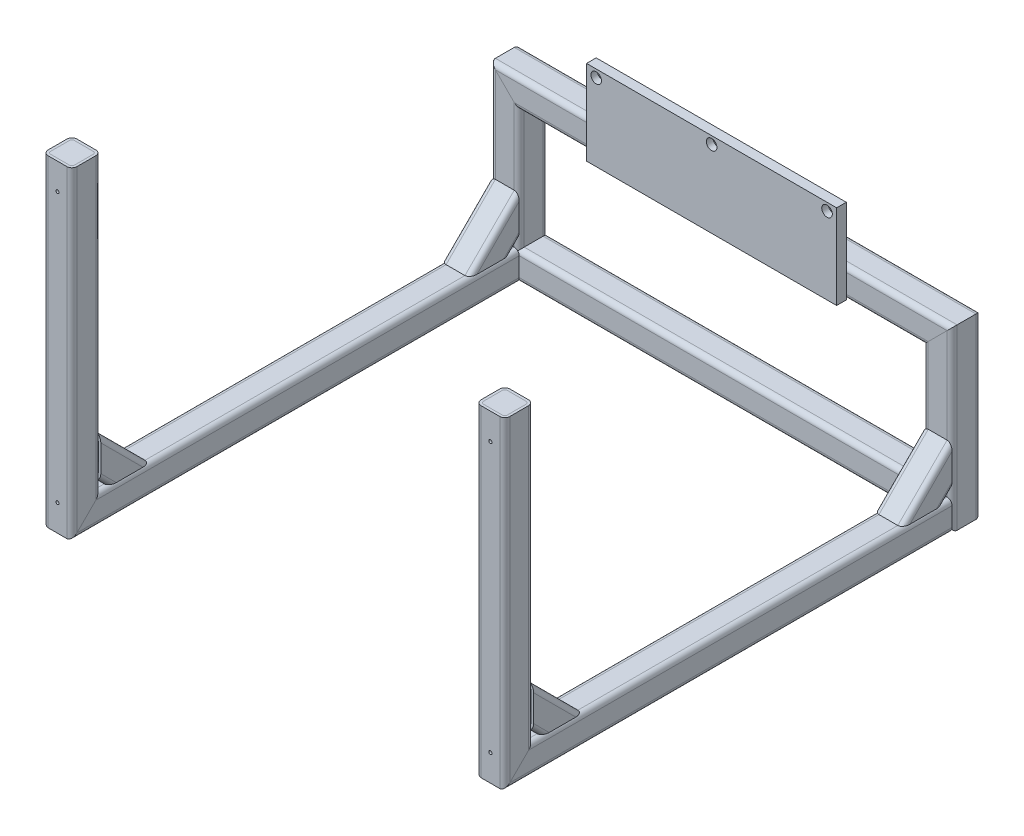
SolidWorks part; units mm, degrees
material "Q235"
ref_plane "前视" through (0, 0, 0) normal (0, 0, 1) x (1, 0, 0)
ref_plane "上视" through (0, 0, 0) normal (0, 1, 0) x (1, 0, 0)
ref_plane "右视" through (0, 0, 0) normal (1, 0, 0) x (0, 0, -1)
sketch3d "3D草图1"
  line L0 (0, 0, 0) -> (0, 0, -67.6759) construction
  line L1 (-225, 0, 0) -> (225, 0, 0)
  line L2 (-225, 0, 0) -> (-225, -155, 0)
  line L3 (-225, -155, 0) -> (-225, -155, 465)
  line L4 (-225, -155, 465) -> (-225, 165, 465)
  line L5 (225, 0, 0) -> (225, -155, 0)
  line L6 (225, -155, 0) -> (225, -155, 465)
  line L7 (225, -155, 465) -> (225, 165, 465)
  line L8 (-225, -155, 0) -> (225, -155, 0)
  line L9 (-225, 165, 465) -> (225, 165, 465) construction
  line L10 (-225, -155, 465) -> (225, -155, 465) construction
  line L11 (-225, -95, 465) -> (-225, -155, 405)
  line L12 (-225, -95, 0) -> (-225, -155, 60)
  line L13 (225, -95, 0) -> (225, -155, 60)
  line L14 (225, -95, 465) -> (225, -155, 405)
  line L15 (-225, -155, 60) -> (225, -155, 60) construction
  line L16 (-225, -155, 405) -> (225, -155, 405) construction
  line L17 (-225, -95, 465) -> (225, -95, 465) construction
  line L18 (-225, -95, 0) -> (225, -95, 0) construction
  dimension "D1" = 450
  dimension "D2" = 465
  dimension "D3" = 320
  dimension "D4" = 155
  dimension "D5" = 45
  dimension "D6" = 45
  dimension "D7" = 60
  dimension "D8" = 60
other "结构构件5"
ref_plane "基准面7" through (-225, 0, 0) normal (0, -1, 0) x (1, 0, 0)
sketch "Sketch1" plane through (-225, 0, 0) normal (0, -1, 0) x (1, 0, 0)
  line L0 (-9.8, -12.4) -> (9.8, -12.4)
  line L1 (-12.4, -9.8) -> (-12.4, 9.8)
  line L2 (9.8, 12.4) -> (-9.8, 12.4)
  line L3 (12.4, 9.8) -> (12.4, -9.8)
  line L4 (-9.8, -15) -> (9.8, -15)
  line L5 (-15, -9.8) -> (-15, 9.8)
  line L6 (9.8, 15) -> (-9.8, 15)
  line L7 (15, 9.8) -> (15, -9.8)
  arc A0 (15, 9.8) -> (9.8, 15) centre (9.8, 9.8) ccw
  arc A1 (9.8, -15) -> (15, -9.8) centre (9.8, -9.8) ccw
  arc A2 (-15, -9.8) -> (-9.8, -15) centre (-9.8, -9.8) ccw
  arc A3 (-9.8, 15) -> (-15, 9.8) centre (-9.8, 9.8) ccw
  arc A4 (-9.8, 12.4) -> (-12.4, 9.8) centre (-9.8, 9.8) ccw
  arc A5 (12.4, 9.8) -> (9.8, 12.4) centre (9.8, 9.8) ccw
  arc A6 (9.8, -12.4) -> (12.4, -9.8) centre (9.8, -9.8) ccw
  arc A7 (-12.4, -9.8) -> (-9.8, -12.4) centre (-9.8, -9.8) ccw
  point P0 (-15, 0)
  point P1 (15, 0)
  point P2 (0, 15)
  point P3 (0, -15)
  point P4 (0, 0)
  point P5 (-15, -15)
  point P6 (15, -15)
  point P7 (15, 15)
  point P8 (-15, 15)
  point P33 (0, 0)
  dimension "D1" = 5.2
  dimension "Thickness" = 2.6
  dimension "V_leg" = 30
other "结构构件6"
ref_plane "基准面8" through (225, -155, 0) normal (0, 0, 1) x (1, 0, 0)
sketch "Sketch15" plane through (225, -155, 0) normal (0, 0, 1) x (1, 0, 0)
  line L0 (-9.8, -12.4) -> (9.8, -12.4)
  line L1 (-12.4, -9.8) -> (-12.4, 9.8)
  line L2 (9.8, 12.4) -> (-9.8, 12.4)
  line L3 (12.4, 9.8) -> (12.4, -9.8)
  line L4 (-9.8, -15) -> (9.8, -15)
  line L5 (-15, -9.8) -> (-15, 9.8)
  line L6 (9.8, 15) -> (-9.8, 15)
  line L7 (15, 9.8) -> (15, -9.8)
  arc A0 (15, 9.8) -> (9.8, 15) centre (9.8, 9.8) ccw
  arc A1 (9.8, -15) -> (15, -9.8) centre (9.8, -9.8) ccw
  arc A2 (-15, -9.8) -> (-9.8, -15) centre (-9.8, -9.8) ccw
  arc A3 (-9.8, 15) -> (-15, 9.8) centre (-9.8, 9.8) ccw
  arc A4 (-9.8, 12.4) -> (-12.4, 9.8) centre (-9.8, 9.8) ccw
  arc A5 (12.4, 9.8) -> (9.8, 12.4) centre (9.8, 9.8) ccw
  arc A6 (9.8, -12.4) -> (12.4, -9.8) centre (9.8, -9.8) ccw
  arc A7 (-12.4, -9.8) -> (-9.8, -12.4) centre (-9.8, -9.8) ccw
  point P0 (-15, 0)
  point P1 (15, 0)
  point P2 (0, 15)
  point P3 (0, -15)
  point P4 (0, 0)
  point P5 (-15, -15)
  point P6 (15, -15)
  point P7 (15, 15)
  point P8 (-15, 15)
  point P33 (0, 0)
  dimension "D1" = 5.2
  dimension "Thickness" = 2.6
  dimension "V_leg" = 30
other "结构构件7"
ref_plane "基准面9" through (-225, -155, 0) normal (0, 0, 1) x (1, 0, 0)
sketch "Sketch16" plane through (-225, -155, 0) normal (0, 0, 1) x (1, 0, 0)
  line L0 (-9.8, -12.4) -> (9.8, -12.4)
  line L1 (-12.4, -9.8) -> (-12.4, 9.8)
  line L2 (9.8, 12.4) -> (-9.8, 12.4)
  line L3 (12.4, 9.8) -> (12.4, -9.8)
  line L4 (-9.8, -15) -> (9.8, -15)
  line L5 (-15, -9.8) -> (-15, 9.8)
  line L6 (9.8, 15) -> (-9.8, 15)
  line L7 (15, 9.8) -> (15, -9.8)
  arc A0 (15, 9.8) -> (9.8, 15) centre (9.8, 9.8) ccw
  arc A1 (9.8, -15) -> (15, -9.8) centre (9.8, -9.8) ccw
  arc A2 (-15, -9.8) -> (-9.8, -15) centre (-9.8, -9.8) ccw
  arc A3 (-9.8, 15) -> (-15, 9.8) centre (-9.8, 9.8) ccw
  arc A4 (-9.8, 12.4) -> (-12.4, 9.8) centre (-9.8, 9.8) ccw
  arc A5 (12.4, 9.8) -> (9.8, 12.4) centre (9.8, 9.8) ccw
  arc A6 (9.8, -12.4) -> (12.4, -9.8) centre (9.8, -9.8) ccw
  arc A7 (-12.4, -9.8) -> (-9.8, -12.4) centre (-9.8, -9.8) ccw
  point P0 (-15, 0)
  point P1 (15, 0)
  point P2 (0, 15)
  point P3 (0, -15)
  point P4 (0, 0)
  point P5 (-15, -15)
  point P6 (15, -15)
  point P7 (15, 15)
  point P8 (-15, 15)
  point P33 (0, 0)
  dimension "D1" = 5.2
  dimension "Thickness" = 2.6
  dimension "V_leg" = 30
other "结构构件8"
ref_plane "基准面10" through (-225, -95, 465) normal (0, -0.7071, -0.7071) x (1, 0, 0)
sketch "Sketch17" plane through (-225, -95, 465) normal (0, -0.7071, -0.7071) x (1, 0, 0)
  line L0 (-9.8, -12.4) -> (9.8, -12.4)
  line L1 (-12.4, -9.8) -> (-12.4, 9.8)
  line L2 (9.8, 12.4) -> (-9.8, 12.4)
  line L3 (12.4, 9.8) -> (12.4, -9.8)
  line L4 (-9.8, -15) -> (9.8, -15)
  line L5 (-15, -9.8) -> (-15, 9.8)
  line L6 (9.8, 15) -> (-9.8, 15)
  line L7 (15, 9.8) -> (15, -9.8)
  arc A0 (15, 9.8) -> (9.8, 15) centre (9.8, 9.8) ccw
  arc A1 (9.8, -15) -> (15, -9.8) centre (9.8, -9.8) ccw
  arc A2 (-15, -9.8) -> (-9.8, -15) centre (-9.8, -9.8) ccw
  arc A3 (-9.8, 15) -> (-15, 9.8) centre (-9.8, 9.8) ccw
  arc A4 (-9.8, 12.4) -> (-12.4, 9.8) centre (-9.8, 9.8) ccw
  arc A5 (12.4, 9.8) -> (9.8, 12.4) centre (9.8, 9.8) ccw
  arc A6 (9.8, -12.4) -> (12.4, -9.8) centre (9.8, -9.8) ccw
  arc A7 (-12.4, -9.8) -> (-9.8, -12.4) centre (-9.8, -9.8) ccw
  point P0 (-15, 0)
  point P1 (15, 0)
  point P2 (0, 15)
  point P3 (0, -15)
  point P4 (0, 0)
  point P5 (-15, -15)
  point P6 (15, -15)
  point P7 (15, 15)
  point P8 (-15, 15)
  point P33 (0, 0)
  dimension "D1" = 5.2
  dimension "Thickness" = 2.6
  dimension "V_leg" = 30
other "结构构件9"
ref_plane "基准面11" through (-225, -95, 0) normal (0, -0.7071, 0.7071) x (1, 0, 0)
sketch "Sketch18" plane through (-225, -95, 0) normal (0, -0.7071, 0.7071) x (1, 0, 0)
  line L0 (-9.8, -12.4) -> (9.8, -12.4)
  line L1 (-12.4, -9.8) -> (-12.4, 9.8)
  line L2 (9.8, 12.4) -> (-9.8, 12.4)
  line L3 (12.4, 9.8) -> (12.4, -9.8)
  line L4 (-9.8, -15) -> (9.8, -15)
  line L5 (-15, -9.8) -> (-15, 9.8)
  line L6 (9.8, 15) -> (-9.8, 15)
  line L7 (15, 9.8) -> (15, -9.8)
  arc A0 (15, 9.8) -> (9.8, 15) centre (9.8, 9.8) ccw
  arc A1 (9.8, -15) -> (15, -9.8) centre (9.8, -9.8) ccw
  arc A2 (-15, -9.8) -> (-9.8, -15) centre (-9.8, -9.8) ccw
  arc A3 (-9.8, 15) -> (-15, 9.8) centre (-9.8, 9.8) ccw
  arc A4 (-9.8, 12.4) -> (-12.4, 9.8) centre (-9.8, 9.8) ccw
  arc A5 (12.4, 9.8) -> (9.8, 12.4) centre (9.8, 9.8) ccw
  arc A6 (9.8, -12.4) -> (12.4, -9.8) centre (9.8, -9.8) ccw
  arc A7 (-12.4, -9.8) -> (-9.8, -12.4) centre (-9.8, -9.8) ccw
  point P0 (-15, 0)
  point P1 (15, 0)
  point P2 (0, 15)
  point P3 (0, -15)
  point P4 (0, 0)
  point P5 (-15, -15)
  point P6 (15, -15)
  point P7 (15, 15)
  point P8 (-15, 15)
  point P33 (0, 0)
  dimension "D1" = 5.2
  dimension "Thickness" = 2.6
  dimension "V_leg" = 30
other "剪裁/延伸1"
other "剪裁/延伸2"
other "剪裁/延伸3"
sketch "草图10" plane through (0, 0, 15) normal (0, 0, 1) x (1, 0, 0)
  line L0 (0, -15) -> (0, 62.0247) construction
  line L1 (-210, -15) -> (210, -15) construction
  line L3 (-130, 73) -> (130, 73)
  line L4 (-130, 73) -> (-130, -15)
  line L5 (-130, -15) -> (130, -15)
  line L6 (130, 73) -> (130, -15)
  line L7 (-130, 73) -> (130, -15) construction
  line L8 (-130, -15) -> (130, 73) construction
  point P5 (0, 29)
  dimension "D1" = 260
  dimension "D2" = 88
extrude "凸台-拉伸1" add sketch "草图10" along normal blind 10 separate body
hole_wizard "打孔尺寸根据内六角圆柱头螺钉的类型1" positions "草图12" profile "草图11" counterbore size "M6" standard "Gb"
sketch "草图12" plane through (0, 0, 25) normal (0, 0, 1) x (1, 0, 0)
  line L0 (0, 73) -> (0, 12.8211) construction
  line L1 (130, 73) -> (-130, 73) construction
  point P0 (-120, 65)
  point P10 (120, 65)
  point P11 (0, 65)
  dimension "D1" = 240
  dimension "D2" = 8
sketch "草图11" plane through (-120, 65, 25) normal (1, 0, 0) x (0, -1, 0)
  line L0 (0, 0) -> (0, 40)
  line L1 (0, 40) -> (3.3, 40)
  line L3 (3.3, 40) -> (3.3, 6.8)
  line L4 (3.3, 6.8) -> (5.5, 6.8)
  line L5 (5.5, 6.8) -> (5.5, 0)
  line L7 (5.5, 0) -> (0, 0)
  line L11 (0, -6.35) -> (0, 107.95) construction
  dimension "通孔孔直径" = 6.6
  dimension "通孔孔深度" = 40
  dimension "柱形沉头孔直径" = 11
  dimension "柱形沉头孔深度" = 6.8
hole_wizard "M4 螺纹孔1" positions "草图14" profile "草图13" tap size "M4" standard "Gb"
sketch "草图14" plane through (0, 0, 480) normal (0, 0, 1) x (1, 0, 0)
  line L0 (-215.2, -2.5) -> (-379.4446, -2.5) construction
  line L1 (-215.2, 165) -> (-215.2, -170) construction
  line L2 (0, -145.2) -> (0, -229.962) construction
  line L3 (215.2, -145.2) -> (-215.2, -145.2) construction
  line L4 (-225, 165) -> (-225, 204.614) construction
  line L5 (-234.8, 165) -> (-215.2, 165) construction
  point P0 (-225, 137.5)
  point P20 (-225, -142.5)
  point P22 (225, -142.5)
  point P23 (225, 137.5)
  dimension "D1" = 280
sketch "草图13" plane through (-225, 137.5, 480) normal (1, 0, 0) x (0, -1, 0)
  line L0 (0, 0) -> (0, 11.0914)
  line L1 (0, 11.0914) -> (1.65, 10.1)
  line L2 (1.65, 10.1) -> (1.65, 0)
  line L5 (1.65, 0) -> (0, 0)
  line L10 (0, 11.0914) -> (-1.65, 10.1) construction
  line L11 (0, -6.35) -> (0, 107.95) construction
  dimension "螺纹孔钻头直径" = 3.3
  dimension "螺纹孔钻头深度" = 10.1
  dimension "导头角度" = 118
cosmetic thread "孔螺蚊线1" parameters "D1"=2.6, "D2"=4
cosmetic thread "孔螺蚊线2" parameters "D1"=2.6, "D2"=4
cosmetic thread "孔螺蚊线3" parameters "D1"=2.6, "D2"=4
cosmetic thread "孔螺蚊线4" parameters "D1"=2.6, "D2"=4
sketch "草图15" plane through (0, 165, 0) normal (0, 1, 0) x (1, 0, 0)
  line L0 (-215.2, -452.6) -> (-234.8, -452.6) construction
  line L1 (-212.6, -474.8) -> (-212.6, -15) construction
  line L2 (-234.8, -477.4) -> (-215.2, -477.4) construction
  line L3 (-237.4, -474.8) -> (-237.4, -15) construction
  line L4 (-215.2, -452.6) -> (-234.8, -452.6)
  line L5 (-212.6, -474.8) -> (-212.6, -455.2)
  line L6 (-234.8, -477.4) -> (-215.2, -477.4)
  line L7 (-237.4, -474.8) -> (-237.4, -455.2)
  line L8 (0, -9.8) -> (0, -379.2185) construction
  line L9 (-240, -9.8) -> (240, -9.8) construction
  line L10 (237.4, -474.8) -> (237.4, -455.2)
  line L11 (234.8, -477.4) -> (215.2, -477.4)
  line L12 (212.6, -474.8) -> (212.6, -455.2)
  line L13 (215.2, -452.6) -> (234.8, -452.6)
  arc A0 (-212.6, -455.2) -> (-215.2, -452.6) centre (-215.2, -455.2) ccw construction
  arc A1 (-215.2, -477.4) -> (-212.6, -474.8) centre (-215.2, -474.8) ccw construction
  arc A2 (-237.4, -474.8) -> (-234.8, -477.4) centre (-234.8, -474.8) ccw construction
  arc A3 (-234.8, -452.6) -> (-237.4, -455.2) centre (-234.8, -455.2) ccw construction
  arc A4 (-212.6, -455.2) -> (-215.2, -452.6) centre (-215.2, -455.2) ccw
  arc A5 (-215.2, -477.4) -> (-212.6, -474.8) centre (-215.2, -474.8) ccw
  arc A6 (-237.4, -474.8) -> (-234.8, -477.4) centre (-234.8, -474.8) ccw
  arc A7 (-234.8, -452.6) -> (-237.4, -455.2) centre (-234.8, -455.2) ccw
  arc A8 (234.8, -452.6) -> (237.4, -455.2) centre (234.8, -455.2) cw
  arc A9 (237.4, -474.8) -> (234.8, -477.4) centre (234.8, -474.8) cw
  arc A10 (215.2, -477.4) -> (212.6, -474.8) centre (215.2, -474.8) cw
  arc A11 (212.6, -455.2) -> (215.2, -452.6) centre (215.2, -455.2) cw
extrude "凸台-拉伸2" add sketch "草图15" against normal blind 2 separate body
